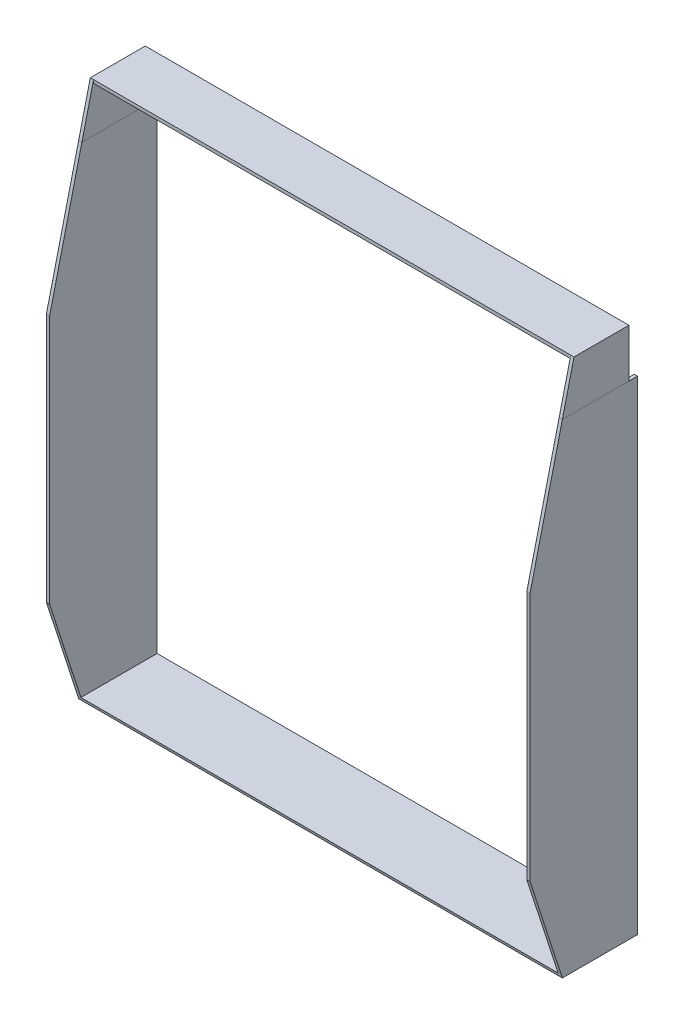
SolidWorks part; units mm, degrees
ref_plane "Plan de face" through (0, 0, 0) normal (0, 0, 1) x (1, 0, 0)
ref_plane "Plan de dessus" through (0, 0, 0) normal (0, 1, 0) x (1, 0, 0)
ref_plane "Plan de droite" through (0, 0, 0) normal (1, 0, 0) x (0, 0, -1)
sketch "Esquisse1" plane through (0, 0, 0) normal (0, 0, 1) x (1, 0, 0)
  line L0 (-447.3, -5.25) -> (-447.3, -449.55)
  line L1 (-450.3, -2.25) -> (-447.3, -2.25)
  line L2 (-450.3, -2.25) -> (-450.3, -452.55)
  line L3 (-450.3, -452.55) -> (0, -452.55)
  line L4 (0, -2.25) -> (0, -452.55)
  line L5 (-447.3, -449.55) -> (-3, -449.55)
  line L6 (-3, -5.25) -> (-3, -449.55)
  line L8 (-3, -5.25) -> (-3, -2.25)
  line L9 (-447.3, -5.25) -> (-447.3, -2.25)
  line L10 (-3, -2.25) -> (0, -2.25)
  line L12 (-450.3, -2.25) -> (0, -2.25) construction
  line L13 (-447.3, -5.25) -> (-3, -5.25) construction
  dimension "D1" = 3
extrude "Boss.-Extru.1" add sketch "Esquisse1" along normal blind 100
sketch "Esquisse2" plane through (0, 0, 0) normal (1, 0, 0) x (0, 0, -1)
  line L0 (-70, -452.55) -> (-100, -359.9029)
  line L1 (-100, -452.55) -> (0, -452.55) construction
  line L2 (-100, -452.55) -> (-100, -2.25) construction
  line L4 (-39, -359.55) -> (-5, -464.55) construction
  line L5 (-70, -452.55) -> (-100, -452.55)
  line L6 (-100, -452.55) -> (-100, -359.9029)
  line L7 (-100, -127.05) -> (-70, -2.25)
  line L8 (-100, -2.25) -> (0, -2.25) construction
  line L9 (-17.2452, -3.75) -> (-39, -94.25) construction
  line L10 (-70, -2.25) -> (-100, -2.25)
  line L11 (-100, -2.25) -> (-100, -127.05)
  dimension "D1" = 30
  dimension "D2" = 30
extrude "Enlèv. mat.-Extru.1" cut sketch "Esquisse2" against normal blind 496
sketch "Esquisse9" plane through (-450.3, 0, 0) normal (-1, 0, 0) x (0, 0, 1)
  line L0 (8, -2.25) -> (70, -2.25)
  line L1 (70, -2.25) -> (59.1827, 42.75)
  line L2 (59.1827, 42.75) -> (8, 42.75)
  line L3 (8, 41.75) -> (8, 5.75) construction
  line L4 (8, 42.75) -> (8, -2.25)
  line L5 (100, -127.05) -> (70, -2.25) construction
  dimension "D1" = 45
extrude "Boss.-Extru.8" add sketch "Esquisse9" against normal blind 3 separate body
sketch "Esquisse10" plane through (0, 0, 0) normal (1, 0, 0) x (0, 0, -1)
  line L0 (-8, -2.25) -> (-70, -2.25)
  line L1 (-70, -2.25) -> (-59.1827, 42.75)
  line L2 (-59.1827, 42.75) -> (-8, 42.75)
  line L3 (-8, 42.75) -> (-8, -2.25)
extrude "Boss.-Extru.9" add sketch "Esquisse10" against normal blind 3 separate body
sketch "Esquisse11" plane through (-3, 0, 0) normal (-1, 0, 0) x (0, 0, 1)
  line L1 (8, 42.75) -> (59.1827, 42.75)
  line L2 (8, 42.75) -> (8, 39.75)
  line L3 (8, 39.75) -> (59.1827, 39.75)
  line L4 (59.1827, 42.75) -> (59.1827, 39.75)
  dimension "D1" = 3
extrude "Boss.-Extru.10" add sketch "Esquisse11" along normal up to surface (444.3 mm away) up to face at (-447.3, -231.7588, 56.8286)
